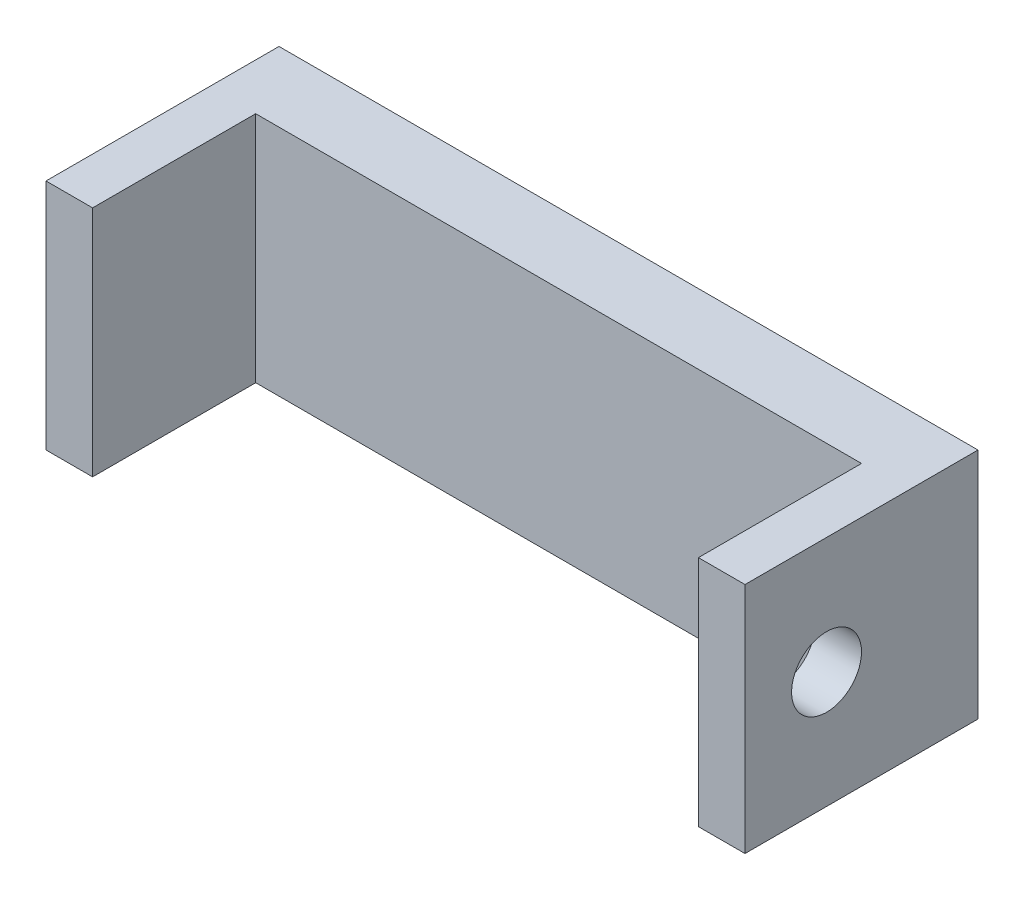
SolidWorks part; units mm, degrees
ref_plane "前视基准面" through (0, 0, 0) normal (0, 0, 1) x (1, 0, 0)
ref_plane "上视基准面" through (0, 0, 0) normal (0, 1, 0) x (1, 0, 0)
ref_plane "右视基准面" through (0, 0, 0) normal (1, 0, 0) x (0, 0, -1)
other "Configuration Table"
sketch "草图1" plane through (0, 0, 0) normal (0, 0, 1) x (1, 0, 0)
  line L5 (-15, 5) -> (15, 5)
  line L6 (-15, 5) -> (-15, -5)
  line L7 (-15, -5) -> (15, -5)
  line L8 (15, 5) -> (15, -5)
  line L9 (-15, 5) -> (15, -5) construction
  line L10 (-15, -5) -> (15, 5) construction
  point P0 (0, 0)
  point P5 (0, 0)
  dimension "D1" = 30
  dimension "D2" = 10
extrude "凸台-拉伸1" add sketch "草图1" along normal mid plane 3
sketch "草图2" plane through (0, 0, 1.5) normal (0, 0, 1) x (1, 0, 0)
  line L0 (-15, 5) -> (-15, -5) construction
  line L1 (-15, 5) -> (-13, 5)
  line L2 (-15, 5) -> (-15, -5)
  line L3 (-15, -5) -> (-13, -5)
  line L4 (-13, 5) -> (-13, -5)
  line L5 (-15, 5) -> (-13, -5) construction
  line L6 (-15, -5) -> (-13, 5) construction
  line L7 (13, 5) -> (15, 5)
  line L8 (13, 5) -> (13, -5)
  line L9 (13, -5) -> (15, -5)
  line L10 (15, 5) -> (15, -5)
  line L11 (13, 5) -> (15, -5) construction
  line L12 (13, -5) -> (15, 5) construction
  line L13 (15, 5) -> (-15, 5) construction
  line L14 (15, -5) -> (15, 5) construction
  point P0 (-14, 0)
  point P5 (14, 0)
  dimension "D1" = 10
  dimension "D2" = 2
  dimension "D3" = 10
  dimension "D4" = 2
extrude "凸台-拉伸2" add sketch "草图2" along normal blind 7
sketch "草图3" plane through (15, 0, 0) normal (1, 0, 0) x (0, 0, -1)
  line L0 (-8.5, -5) -> (1.5, -5) construction
  line L5 (-8.5, -5) -> (-8.5, 5) construction
  circle A1 centre (-5, 0) radius 1.5
  dimension "D1" = 3
  dimension "D2" = 3.5
  dimension "D3" = 5
extrude "切除-拉伸1" cut sketch "草图3" against normal up to next
